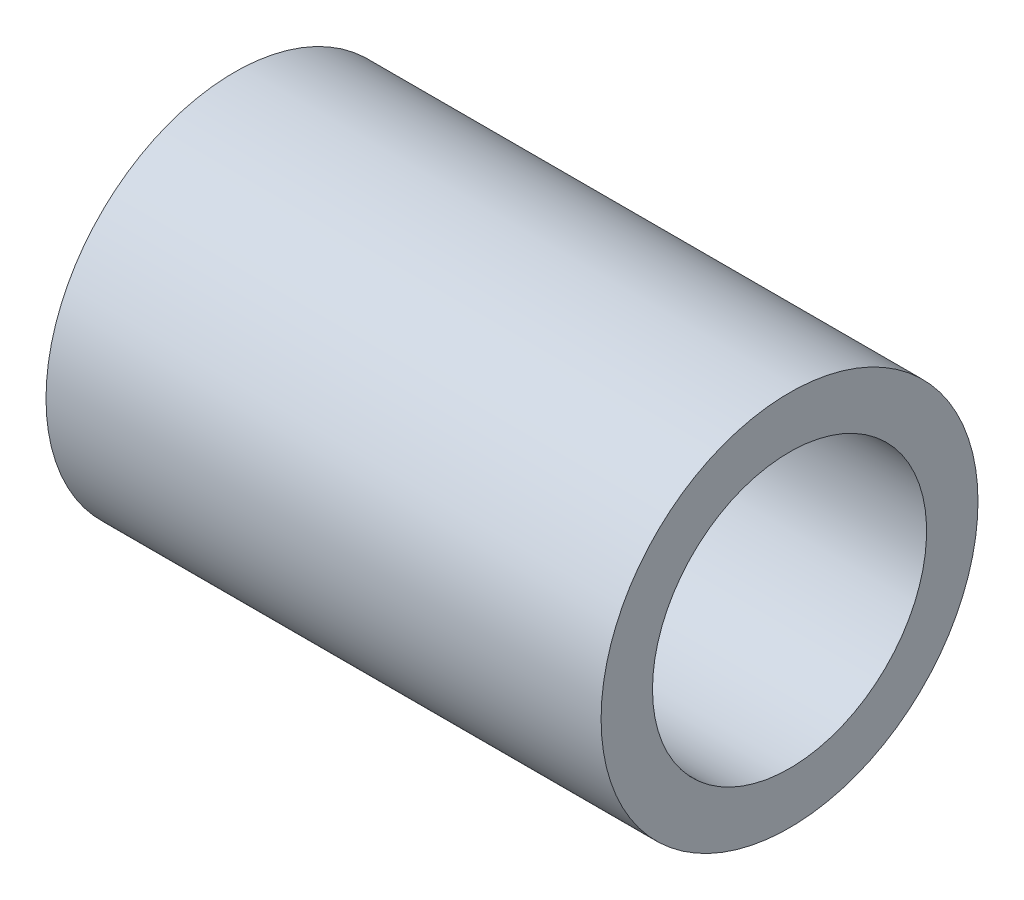
SolidWorks part; units mm, degrees
ref_plane "Front" through (0, 0, 0) normal (0, 0, 1) x (1, 0, 0)
ref_plane "Top" through (0, 0, 0) normal (0, 1, 0) x (1, 0, 0)
ref_plane "Right" through (0, 0, 0) normal (1, 0, 0) x (0, 0, -1)
sketch "Sketch1" plane through (0, 0, 0) normal (0, 0, 1) x (1, 0, 0)
  line L0 (-3.3073, 0) -> (19.1809, 0) construction
  line L2 (0, 0) -> (16.2, 0)
  line L3 (0, 0) -> (0, 5.5)
  line L4 (0, 5.5) -> (16.2, 5.5)
  line L5 (16.2, 0) -> (16.2, 5.5)
  dimension "D1" = 11
  dimension "D2" = 16.2
revolve "Revolve1" add sketch "Sketch1" angle 360 about L0
sketch "Sketch2" plane through (0, 0, 0) normal (0, 0, 1) x (1, 0, 0)
  line L0 (-3.0539, 0) -> (18.1303, 0) construction
  line L1 (16.2, -5.5) -> (16.2, 5.5) construction
  line L2 (0, 0) -> (16.2, 0)
  line L3 (0, 0) -> (0, 4)
  line L4 (0, 4) -> (16.2, 4)
  line L5 (16.2, 0) -> (16.2, 4)
  dimension "D1" = 8
revolve "Cut-Revolve1" cut sketch "Sketch2" angle 360 about L0
